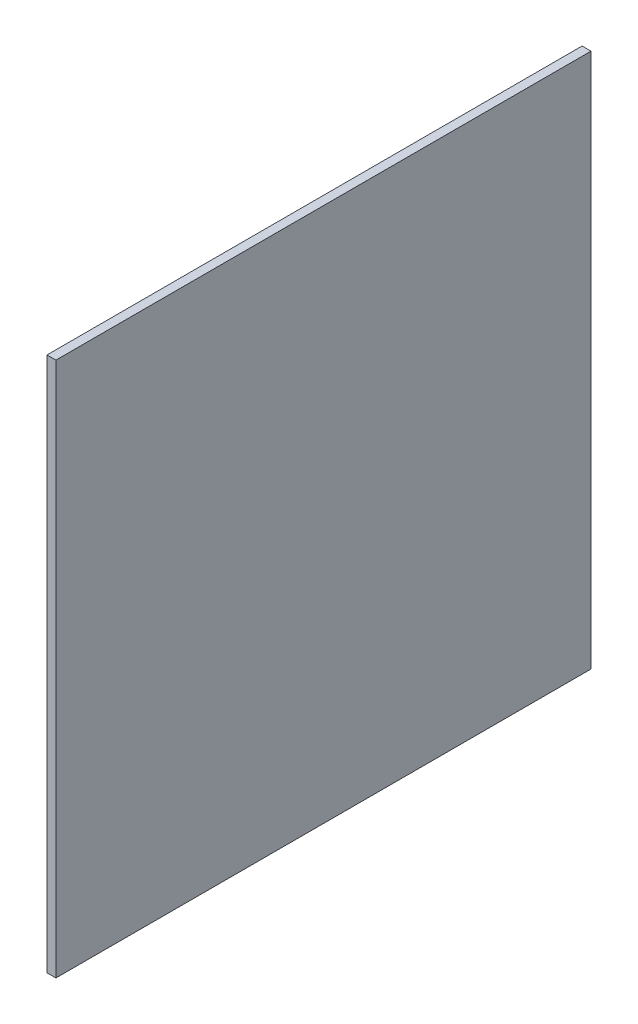
SolidWorks part; units mm, degrees
ref_plane "Front Plane" through (0, 0, 0) normal (0, 0, 1) x (1, 0, 0)
ref_plane "Top Plane" through (0, 0, 0) normal (0, 1, 0) x (1, 0, 0)
ref_plane "Right Plane" through (0, 0, 0) normal (1, 0, 0) x (0, 0, -1)
sketch "Sketch1" plane through (0, 0, 0) normal (1, 0, 0) x (0, 0, -1)
  line L1 (-300, -300) -> (300, -300)
  line L2 (-300, -300) -> (-300, 300)
  line L3 (-300, 300) -> (300, 300)
  line L4 (300, -300) -> (300, 300)
  line L5 (-300, -300) -> (300, 300) construction
  line L6 (-300, 300) -> (300, -300) construction
  point P0 (0, 0)
extrude "Boss-Extrude1" add sketch "Sketch1" along normal blind 10
